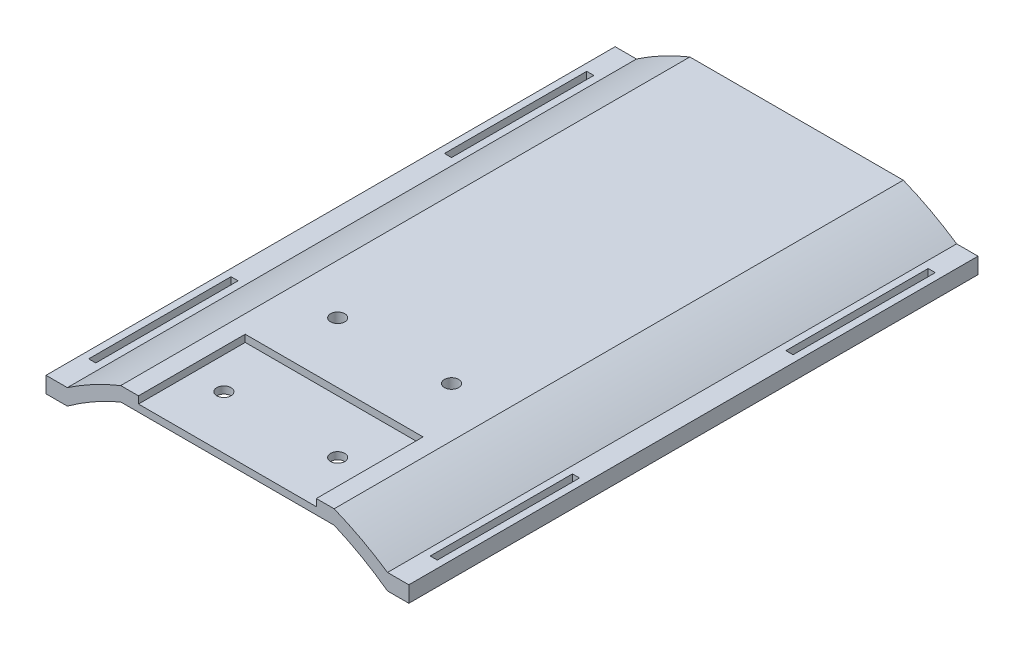
SolidWorks part; units mm, degrees
ref_plane "Front Plane" through (0, 0, 0) normal (0, 0, 1) x (1, 0, 0)
ref_plane "Top Plane" through (0, 0, 0) normal (0, 1, 0) x (1, 0, 0)
ref_plane "Right Plane" through (0, 0, 0) normal (1, 0, 0) x (0, 0, -1)
sketch "Sketch4" plane through (0, 0, 0) normal (0, 0, 1) x (1, 0, 0)
  line L6 (-19.1107, 53.8852) -> (-16.1107, 53.8852)
  line L7 (-8.6107, 57.8852) -> (21.3893, 57.8852)
  line L8 (28.8893, 53.8852) -> (31.8893, 53.8852)
  line L9 (-19.1107, 53.8852) -> (-19.1107, 51.6274)
  line L10 (-19.1107, 51.6274) -> (-16.1107, 51.6274)
  line L11 (-8.6107, 55.8852) -> (21.3893, 55.8852)
  line L12 (28.8893, 51.6274) -> (31.8893, 51.6274)
  line L13 (31.8893, 51.6274) -> (31.8893, 53.8852)
  arc A2 (-16.1107, 53.8852) -> (-8.6107, 57.8852) centre (6.3893, 20.729) cw
  arc A3 (28.8893, 53.8852) -> (21.3893, 57.8852) centre (6.3893, 20.729) ccw
  arc A4 (-16.1107, 51.6274) -> (-8.6107, 55.8852) centre (6.3893, 20.729) cw
  arc A5 (21.3893, 55.8852) -> (28.8893, 51.6274) centre (6.3893, 20.729) cw
  dimension "D11" = 30
  dimension "D3" = 7.5
  dimension "D6" = 7.5
  dimension "D1" = 3
  dimension "D2" = 4
  dimension "D4" = 30
  dimension "D5" = 4
  dimension "D7" = 3
  dimension "D8" = 2
  dimension "D9" = 7.5
  dimension "D10" = 3
  dimension "D12" = 7.5
  dimension "D13" = 3
  dimension "D14" = 2.2578
  dimension "D15" = 2.2578
extrude "Boss-Extrude1" add sketch "Sketch4" along normal blind 80
sketch "Sketch8" plane through (0, 57.8852, 0) normal (0, 1, 0) x (1, 0, 0)
  line L0 (21.3893, -80) -> (-8.6107, -80) construction
  line L1 (-6.1107, -80) -> (18.8893, -80)
  line L2 (-6.1107, -80) -> (-6.1107, -65)
  line L3 (-6.1107, -65) -> (18.8893, -65)
  line L4 (18.8893, -80) -> (18.8893, -65)
  line L5 (-8.6107, -80) -> (-8.6107, 0) construction
  dimension "D1" = 25
  dimension "D2" = 15
  dimension "D3" = 2.5
extrude "Cut-Extrude2" cut sketch "Sketch8" against normal blind 1
sketch "Sketch9" plane through (0, 56.8852, 0) normal (0, 1, 0) x (1, 0, 0)
  line L0 (-6.1107, -65) -> (-6.1107, -80) construction
  line L1 (18.8893, -65) -> (-6.1107, -65) construction
  line L2 (18.8893, -80) -> (18.8893, -65) construction
  circle A0 centre (-1.6107, -72.5) radius 1
  circle A1 centre (14.3893, -72.5) radius 1
  dimension "D1" = 4.5
  dimension "D2" = 7.5
  dimension "D3" = 4.5
  dimension "D4" = 7.5
extrude "Cut-Extrude3" cut sketch "Sketch9" against normal blind 1
ref_plane "Plane31" through (0, 51.63, 0) normal (0, 1, 0) x (1, 0, 0)
sketch "Sketch12" plane through (0, 53.8852, 0) normal (0, 1, 0) x (1, 0, 0)
  line L0 (-19.1107, -80) -> (-19.1107, 0) construction
  line L1 (-18.1107, -5) -> (-17.1107, -5)
  line L2 (-18.1107, -5) -> (-18.1107, -25)
  line L3 (-18.1107, -25) -> (-17.1107, -25)
  line L4 (-17.1107, -5) -> (-17.1107, -25)
  line L5 (-16.1107, 0) -> (-19.1107, 0) construction
  line L6 (-18.1107, -55) -> (-17.1107, -55)
  line L7 (-18.1107, -55) -> (-18.1107, -75)
  line L8 (-18.1107, -75) -> (-17.1107, -75)
  line L9 (-17.1107, -55) -> (-17.1107, -75)
  line L10 (-16.1107, -80) -> (-19.1107, -80) construction
  line L11 (-16.1107, -80) -> (-16.1107, 0) construction
  line L12 (29.8893, -5) -> (30.8893, -5)
  line L13 (29.8893, -5) -> (29.8893, -25)
  line L14 (29.8893, -25) -> (30.8893, -25)
  line L15 (30.8893, -5) -> (30.8893, -25)
  line L16 (29.8893, -55) -> (30.8893, -55)
  line L17 (29.8893, -55) -> (29.8893, -75)
  line L18 (29.8893, -75) -> (30.8893, -75)
  line L19 (30.8893, -55) -> (30.8893, -75)
  line L20 (31.8893, 0) -> (28.8893, 0) construction
  line L21 (28.8893, -80) -> (28.8893, 0) construction
  line L22 (31.8893, -80) -> (28.8893, -80) construction
  line L23 (31.8893, -80) -> (31.8893, 0) construction
  dimension "D1" = 1
  dimension "D2" = 1
  dimension "D3" = 20
  dimension "D4" = 5
  dimension "D5" = 5
  dimension "D6" = 20
  dimension "D7" = 1
  dimension "D8" = 1
  dimension "D9" = 5
  dimension "D10" = 1
  dimension "D11" = 5
  dimension "D12" = 1
  dimension "D13" = 1
  dimension "D14" = 1
  dimension "D15" = 20
  dimension "D16" = 20
extrude "Cut-Extrude4" cut sketch "Sketch12" against normal blind 4.69
sketch "Sketch13" plane through (0, 57.8852, 0) normal (0, 1, 0) x (1, 0, 0)
  circle A0 centre (-1.6107, -56.5) radius 1
  circle A1 centre (-1.6107, -72.5) radius 1 construction
  circle A2 centre (14.3893, -56.5) radius 1
  circle A3 centre (14.3893, -72.5) radius 1 construction
  dimension "D2" = 2
  dimension "D3" = 16
  dimension "D4" = 2
  dimension "D6" = 16
  dimension "D1" = 0
  dimension "D5" = 16
extrude "Cut-Extrude5" cut sketch "Sketch13" against normal blind 4.69
